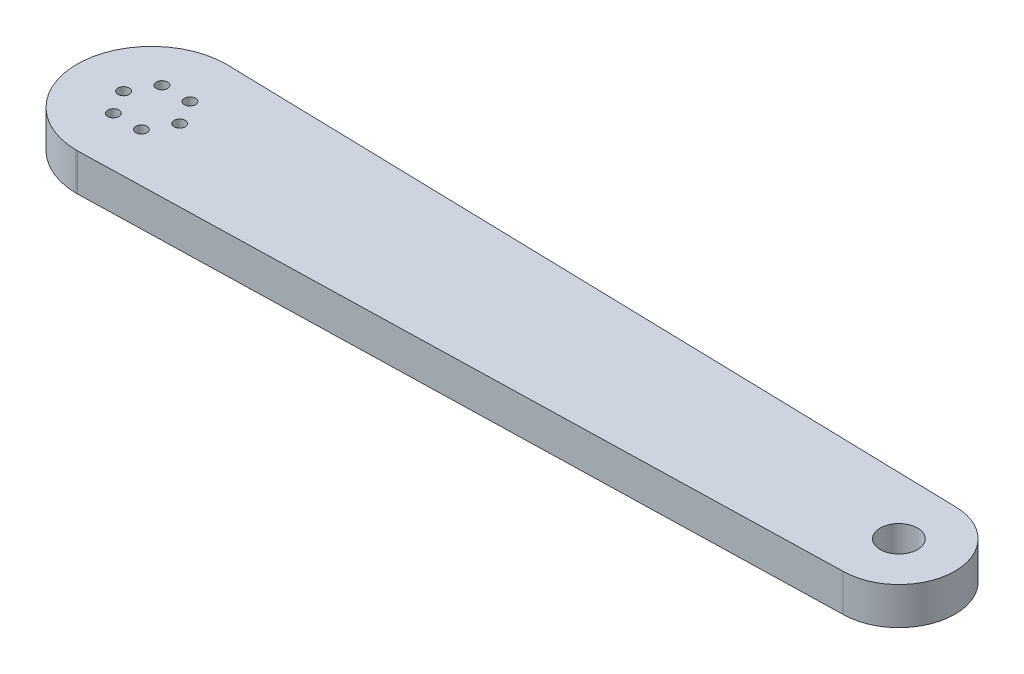
SolidWorks part; units mm, degrees
ref_plane "Alzado" through (0, 0, 0) normal (0, 0, 1) x (1, 0, 0)
ref_plane "Planta" through (0, 0, 0) normal (0, 1, 0) x (1, 0, 0)
ref_plane "Vista lateral" through (0, 0, 0) normal (1, 0, 0) x (0, 0, -1)
sketch "Croquis1" plane through (0, 0, 0) normal (0, 1, 0) x (1, 0, 0)
  line L0 (0.1464, 19.9963) -> (200, 15)
  line L1 (0.1464, -19.9963) -> (200, -15)
  circle A0 centre (0, 0) radius 7.5 construction
  circle A1 centre (7.5, 0) radius 1.5
  circle A2 centre (3.75, -6.4952) radius 1.5
  circle A3 centre (-3.75, -6.4952) radius 1.5
  circle A4 centre (-7.5, 0) radius 1.5
  circle A5 centre (-3.75, 6.4952) radius 1.5
  circle A6 centre (3.75, 6.4952) radius 1.5
  arc A7 (-0.2071, 19.9989) -> (-0.2071, -19.9989) centre (0, 0) ccw
  arc A8 (200, -15) -> (200, 15) centre (200, 0) ccw
  circle A9 centre (200, 0) radius 5
  arc A10 (0.1464, -19.9963) -> (-0.2071, -19.9989) centre (-0.1035, -9.9995) cw
  arc A11 (0.1464, 19.9963) -> (-0.2071, 19.9989) centre (-0.1035, 9.9995) ccw
  point P17 (0, 0)
  point P24 (0, -20)
  point P27 (0, 20)
  dimension "D1" = 15
  dimension "D2" = 3
  dimension "D4" = 40
  dimension "D5" = 200
  dimension "D6" = 15
  dimension "D7" = 10
  dimension "D8" = 10
  dimension "D3" = 6
extrude "Saliente-Extruir1" add sketch "Croquis1" along normal blind 10
